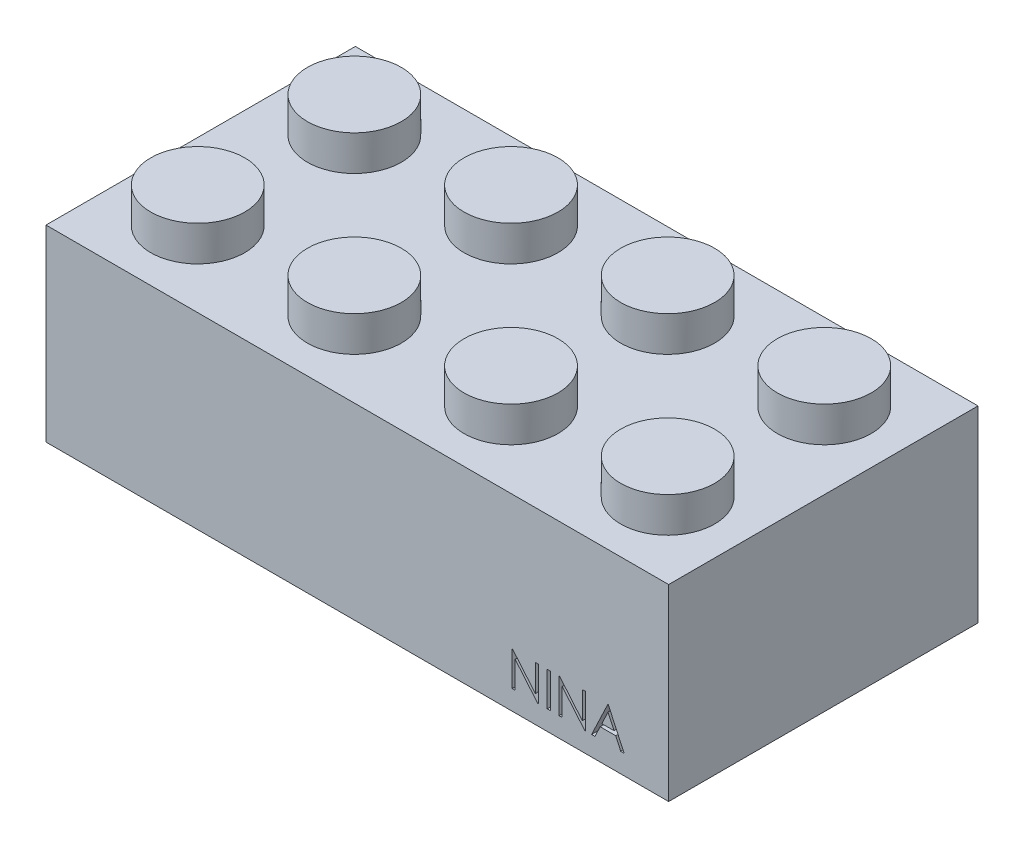
SolidWorks part; units mm, degrees
ref_plane "Front Plane" through (0, 0, 0) normal (0, 0, 1) x (1, 0, 0)
ref_plane "Top Plane" through (0, 0, 0) normal (0, 1, 0) x (1, 0, 0)
ref_plane "Right Plane" through (0, 0, 0) normal (1, 0, 0) x (0, 0, -1)
sketch "Sketch1" plane through (0, 0, 0) normal (0, 1, 0) x (1, 0, 0)
  line L1 (-31.8, -15.8) -> (31.8, -15.8)
  line L2 (-31.8, -15.8) -> (-31.8, 15.8)
  line L3 (-31.8, 15.8) -> (31.8, 15.8)
  line L4 (31.8, -15.8) -> (31.8, 15.8)
  line L5 (-31.8, -15.8) -> (31.8, 15.8) construction
  line L6 (-31.8, 15.8) -> (31.8, -15.8) construction
  point P0 (0, 0)
  dimension "D1" = 63.6
  dimension "D2" = 31.6
extrude "Boss-Extrude1" add sketch "Sketch1" along normal blind 19.2
sketch "Sketch2" plane through (0, 0, 0) normal (0, -1, 0) x (1, 0, 0)
  line L0 (31.8, 15.8) -> (31.8, -15.8) construction
  line L1 (-29.4, 13.4) -> (29.4, 13.4)
  line L2 (-29.4, 13.4) -> (-29.4, -13.4)
  line L3 (-29.4, -13.4) -> (29.4, -13.4)
  line L4 (29.4, 13.4) -> (29.4, -13.4)
  line L5 (-29.4, 13.4) -> (29.4, -13.4) construction
  line L6 (-29.4, -13.4) -> (29.4, 13.4) construction
  line L7 (-31.8, 15.8) -> (31.8, 15.8) construction
  point P0 (0, 0)
  dimension "D1" = 2.4
  dimension "D2" = 2.4
extrude "Cut-Extrude1" cut sketch "Sketch2" against normal blind 17.2
sketch "Sketch3" plane through (0, 19.2, 0) normal (0, 1, 0) x (1, 0, 0)
  line L0 (31.8, -15.8) -> (31.8, 15.8) construction
  line L1 (31.8, 15.8) -> (-31.8, 15.8) construction
  circle A0 centre (24, 7.9) radius 4.8
  dimension "D3" = 9.6
  dimension "D1" = 7.8
  dimension "D2" = 7.9
extrude "Boss-Extrude2" add sketch "Sketch3" along normal blind 3.6
pattern_linear "LPattern1" count 4 spacing 16 along (-1, 0, 0) count 2 spacing 16 along (0, 0, 1) of "Boss-Extrude2"
sketch "Sketch4" plane through (0, 17.2, 0) normal (0, -1, 0) x (-1, 0, 0)
  line L0 (-31.8, -15.8) -> (-31.8, 15.8) construction
  line L1 (31.8, -15.8) -> (-31.8, -15.8) construction
  circle A0 centre (-24, -7.9) radius 2.6
  dimension "D3" = 5.2
  dimension "D1" = 7.8
  dimension "D2" = 7.9
extrude "Cut-Extrude2" cut sketch "Sketch4" against normal blind 3.4 contours A0
pattern_linear "LPattern2" count 4 spacing 16 along (-1, 0, 0) count 2 spacing 16 along (0, 0, -1) of "Cut-Extrude2"
sketch "Sketch5" plane through (0, 17.2, 0) normal (0, -1, 0) x (1, 0, 0)
  circle A0 centre (0, 0) radius 6.51
  circle A1 centre (0, 0) radius 4.8
  dimension "D1" = 13.02
  dimension "D2" = 9.6
extrude "Boss-Extrude3" add sketch "Sketch5" along normal up to surface (17.2 mm away) up to face at (0, 0, 0)
pattern_linear "LPattern3" count 2 spacing 16 along (1, 0, 0) of "Boss-Extrude3"
pattern_linear "LPattern4" count 2 spacing 16 along (-1, 0, 0) of "Boss-Extrude3"
sketch "Sketch6" plane through (0, 17.2, 0) normal (0, -1, 0) x (1, 0, 0)
  line L0 (0, 13.4) -> (0, -13.4) construction
  line L1 (29.4, 13.4) -> (-29.4, 13.4) construction
  line L2 (-29.4, -13.4) -> (29.4, -13.4) construction
  line L3 (-0.8, 13.4) -> (-0.8, -13.4)
  line L4 (0.8, 13.4) -> (0.8, -13.4)
  line L5 (-0.8, 13.4) -> (0.8, 13.4)
  line L6 (-0.8, -13.4) -> (0.8, -13.4)
  circle A0 centre (0, 0) radius 6.51 construction
  circle A1 centre (0, 0) radius 6.51
  circle M5 centre (0, 0) radius 6.51
  line M15 (29.4, 13.4) -> (-29.4, 13.4)
  line M17 (-29.4, -13.4) -> (29.4, -13.4)
  dimension "D1" = 0.8
  dimension "D2" = 0.8
extrude "Boss-Extrude4" add sketch "Sketch6" along normal blind 12.6 contours L0 A1 L4 M15 | L0 L5 L3 M5 | L0 A1 L3 M17 | L0 L6 L4 M5
sketch "Sketch7" plane through (0, 0, 0) normal (0, -1, 0) x (1, 0, 0)
  line L0 (29.4, 13.4) -> (0.8, 13.4) construction
  line L1 (31.8, 15.8) -> (31.8, -15.8) construction
  circle A0 centre (24, 13.4) radius 0.6
  dimension "D1" = 1.2
  dimension "D2" = 7.8
extrude "Boss-Extrude5" add sketch "Sketch7" against normal up to next
pattern_linear "LPattern5" count 4 spacing 16 along (-1, 0, 0) of "Boss-Extrude5"
sketch "Sketch8" plane through (0, 0, 0) normal (0, -1, 0) x (-1, 0, 0)
  line L0 (-29.4, 13.4) -> (-29.4, -13.4) construction
  line L1 (31.8, -15.8) -> (-31.8, -15.8) construction
  circle A0 centre (-29.4, -7.9) radius 0.6
  dimension "D1" = 1.2
  dimension "D2" = 7.9
extrude "Boss-Extrude6" add sketch "Sketch8" against normal up to surface (17.2 mm away) up to face at (13.171, 17.2, 5.24)
mirror "Mirror2" about plane through (0, 0, 0) normal (0, 0, 1) of "LPattern5", "Boss-Extrude5"
sketch "Sketch9" plane through (0, 0, 15.8) normal (0, 0, 1) x (1, 0, 0)
  line L0 (15.3595, 2) -> (31.8, 2) construction
  line L1 (31.8, 19.2) -> (31.8, 0) construction
  line L2 (-31.8, 0) -> (31.8, 0) construction
  text T0 "NINA"
  dimension "D1" = 2
extrude "Cut-Extrude3" cut sketch "Sketch9" against normal blind 2
sketch "Sketch10" plane through (0, 0, 0) normal (0, -1, 0) x (-1, 0, 0)
  line L0 (-29.4, 13.4) -> (-29.4, -7.3) construction
  line L1 (-31.8, 15.8) -> (31.8, 15.8) construction
  circle A0 centre (-29.4, 7.9) radius 0.6
  dimension "D1" = 1.2
  dimension "D2" = 7.9
extrude "Boss-Extrude7" add sketch "Sketch10" against normal up to surface (17.2 mm away) up to face at (15.8694, 17.2, 0.9875)
mirror "Mirror3" about plane through (0, 0, 0) normal (1, 0, 0) of "Boss-Extrude6", "Boss-Extrude7"
